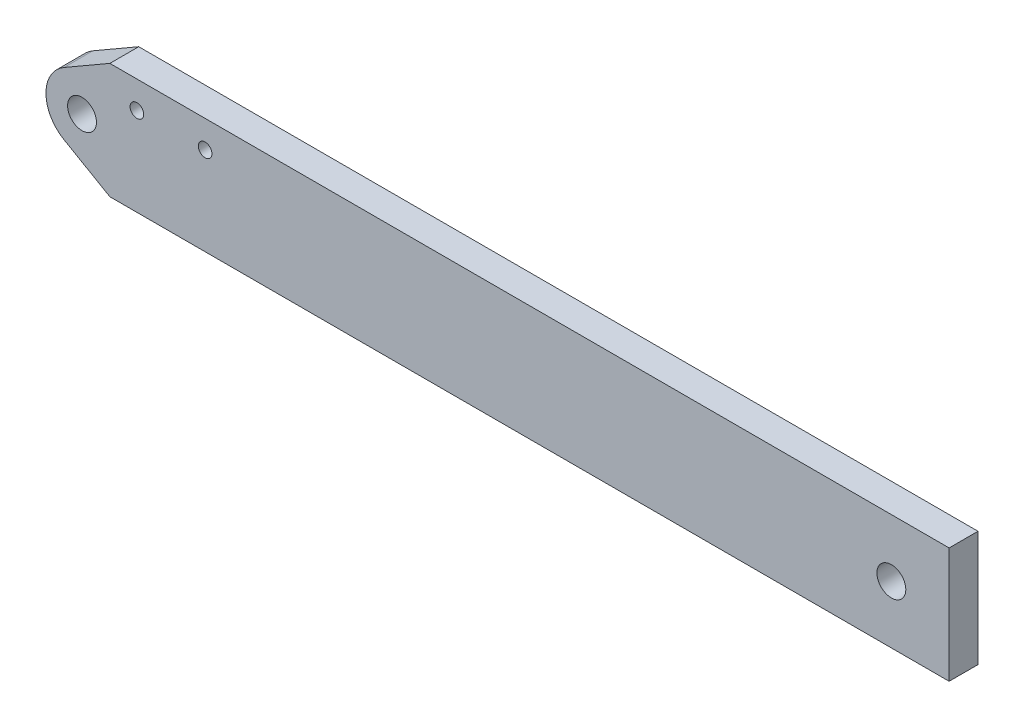
SolidWorks part; units mm, degrees
ref_plane "Front Plane" through (0, 0, 0) normal (0, 0, 1) x (1, 0, 0)
ref_plane "Top Plane" through (0, 0, 0) normal (0, 1, 0) x (1, 0, 0)
ref_plane "Right Plane" through (0, 0, 0) normal (1, 0, 0) x (0, 0, -1)
sketch "Sketch1" plane through (0, 0, 0) normal (1, 0, 0) x (0, 0, -1)
  line L1 (0, 0) -> (6.35, 0)
  line L2 (0, 0) -> (0, 25.4)
  line L3 (0, 25.4) -> (6.35, 25.4)
  line L4 (6.35, 0) -> (6.35, 25.4)
  dimension "D1" = 25.4
  dimension "D2" = 6.35
extrude "Boss-Extrude1" add sketch "Sketch1" along normal blind 200
sketch "Sketch2" plane through (0, 0, 0) normal (0, 0, 1) x (1, 0, 0)
  line L0 (200, 25.4) -> (200, 0) construction
  circle A0 centre (187.3, 12.7) radius 3.175
  point P4 (200, 12.7)
  dimension "D2" = 6.35
  dimension "D1" = 12.7
extrude "Cut-Extrude1" cut sketch "Sketch2" against normal through all
sketch "Sketch3" plane through (0, 0, 0) normal (0, 0, 1) x (1, 0, 0)
  line L0 (0, 25.4) -> (0, 0) construction
  line L1 (15.442, 25.4) -> (-1, 25.4)
  line L2 (200, 25.4) -> (0, 25.4) construction
  line L3 (-1, 25.4) -> (-1, 0)
  line L4 (-1, 0) -> (15.442, 0)
  line L5 (200, 0) -> (0, 0) construction
  line L6 (15.442, 0) -> (5.355, 5.8238)
  line L7 (5.355, 19.5762) -> (15.442, 25.4)
  circle A0 centre (9.325, 12.7) radius 3.175
  arc A1 (5.355, 19.5762) -> (5.355, 5.8238) centre (9.325, 12.7) ccw
  point P4 (0, 12.7)
  dimension "D1" = 6.35
  dimension "D3" = 30
  dimension "D5" = 15.88
  dimension "D2" = 9.325
  dimension "D4" = 1
extrude "Cut-Extrude2" cut sketch "Sketch3" against normal through all
sketch "Sketch6" plane through (0, 0, 0) normal (0, 0, 1) x (1, 0, 0)
  line L0 (200, 25.4) -> (15.442, 25.4) construction
  circle A0 centre (21.385, 19.4) radius 1.5
  circle A1 centre (36.385, 19.4) radius 1.5
  arc A2 (5.355, 19.5762) -> (5.355, 5.8238) centre (9.325, 12.7) ccw construction
  dimension "D1" = 3
  dimension "D2" = 6
  dimension "D3" = 15
  dimension "D4" = 20
extrude "Cut-Extrude3" cut sketch "Sketch6" against normal through all
